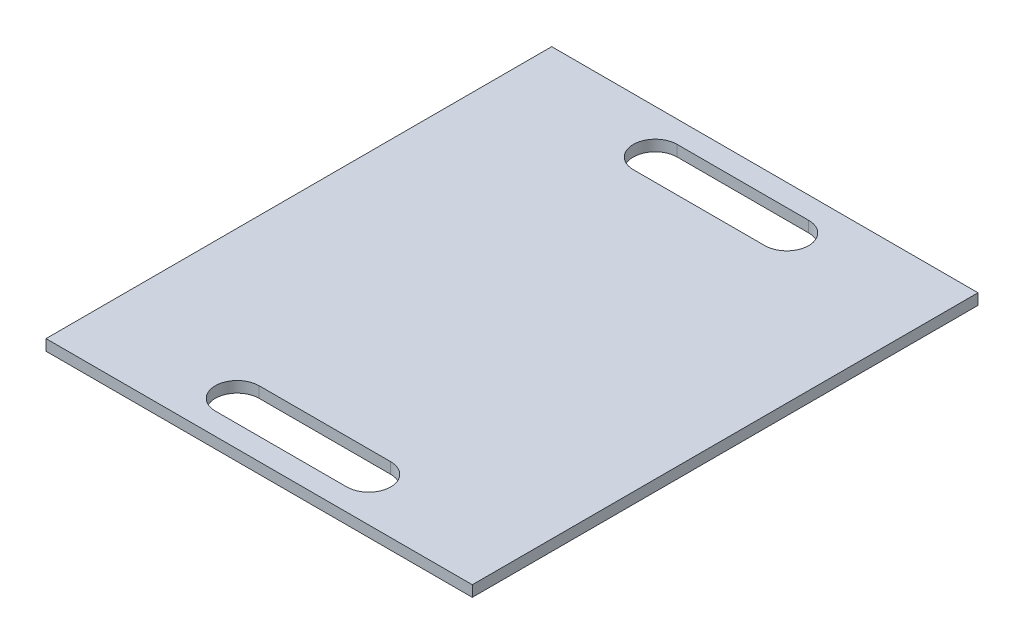
SolidWorks part; units mm, degrees
material "Acrylic (Medium-high impact)"
ref_plane "Front Plane" through (0, 0, 0) normal (0, 0, 1) x (1, 0, 0)
ref_plane "Top Plane" through (0, 0, 0) normal (0, 1, 0) x (1, 0, 0)
ref_plane "Right Plane" through (0, 0, 0) normal (1, 0, 0) x (0, 0, -1)
sketch "Sketch1" plane through (0, 0, 0) normal (0, 1, 0) x (1, 0, 0)
  line L1 (-123.5, -146.5) -> (123.5, -146.5)
  line L2 (-123.5, -146.5) -> (-123.5, 146.5)
  line L3 (-123.5, 146.5) -> (123.5, 146.5)
  line L4 (123.5, -146.5) -> (123.5, 146.5)
  line L5 (-123.5, -146.5) -> (123.5, 146.5) construction
  line L6 (-123.5, 146.5) -> (123.5, -146.5) construction
  point P0 (0, 0)
  dimension "D1" = 293
  dimension "D2" = 247
extrude "Main Base" add sketch "Sketch1" along normal mid plane 6.35
sketch "Sketch2" plane through (0, 3.175, 0) normal (0, 1, 0) x (1, 0, 0)
  line L0 (-38.1, 121.1) -> (38.1, 121.1) construction
  line L1 (-38.1, 133.8) -> (38.1, 133.8)
  line L2 (-38.1, 108.4) -> (38.1, 108.4)
  line L3 (123.5, 146.5) -> (-123.5, 146.5) construction
  line L4 (-1000, 0) -> (49000, 0) construction
  line L5 (-38.1, -121.1) -> (38.1, -121.1) construction
  line L6 (-38.1, -133.8) -> (38.1, -133.8)
  line L7 (-38.1, -108.4) -> (38.1, -108.4)
  arc A0 (-38.1, 133.8) -> (-38.1, 108.4) centre (-38.1, 121.1) ccw
  arc A1 (38.1, 108.4) -> (38.1, 133.8) centre (38.1, 121.1) ccw
  arc A2 (-38.1, -133.8) -> (-38.1, -108.4) centre (-38.1, -121.1) cw
  arc A3 (38.1, -108.4) -> (38.1, -133.8) centre (38.1, -121.1) cw
  point P2 (0, 121.1)
  point P14 (0, -121.1)
  dimension "D2" = 25.4
  dimension "D1" = 25.4
  dimension "D3" = 76.2
extrude "Handles" cut sketch "Sketch2" against normal through all
